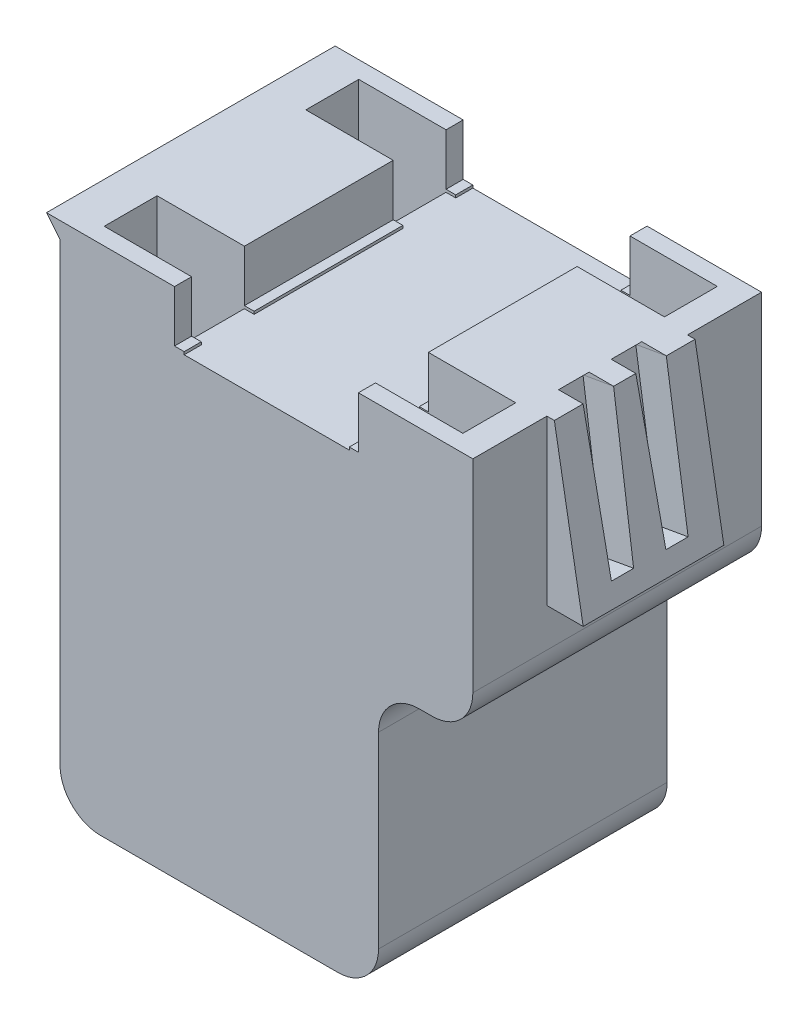
SolidWorks part; units mm, degrees
ref_plane "Alzado" through (0, 0, 0) normal (0, 0, 1) x (1, 0, 0)
ref_plane "Planta" through (0, 0, 0) normal (0, 1, 0) x (1, 0, 0)
ref_plane "Vista lateral" through (0, 0, 0) normal (1, 0, 0) x (0, 0, -1)
sketch "Croquis1" plane through (0, 0, 0) normal (0, 0, 1) x (1, 0, 0)
  line L1 (-15.23, 18.9) -> (-6.785, 18.9)
  line L2 (-15.23, 18.9) -> (-15.23, -15.9)
  line L3 (-12.23, -18.9) -> (5.27, -18.9)
  line L4 (15.23, 18.9) -> (15.23, 3.95)
  line L5 (-15.23, 18.9) -> (8.27, -10.2628) construction
  line L6 (-15.23, -18.9) -> (15.23, 18.9) construction
  line L7 (-6.785, 15.1) -> (6.785, 15.1)
  line L8 (-6.785, 15.1) -> (-6.785, 18.9)
  line L9 (6.785, 15.1) -> (6.785, 18.9)
  line L10 (6.785, 18.9) -> (15.23, 18.9)
  line L11 (8.27, -15.9) -> (8.27, -2.05)
  line L12 (11.27, 0.95) -> (12.23, 0.95)
  arc A0 (15.23, 3.95) -> (12.23, 0.95) centre (12.23, 3.95) cw
  arc A1 (11.27, 0.95) -> (8.27, -2.05) centre (11.27, -2.05) ccw
  arc A2 (5.27, -18.9) -> (8.27, -15.9) centre (5.27, -15.9) ccw
  arc A3 (-12.23, -18.9) -> (-15.23, -15.9) centre (-12.23, -15.9) cw
  point P0 (0, 0)
  point P17 (8.27, 0.95)
  point P20 (8.27, -18.9)
  dimension "D1" = 3
  dimension "D2" = 30.46
  dimension "D4" = 19.85
extrude "Saliente-Extruir1" add sketch "Croquis1" along normal blind 21.3
sketch "Croquis2" plane through (0, 0, 0) normal (0, 0, -1) x (-1, 0, 0)
  line L0 (-15.23, 18.9) -> (-15.7844, 18.9)
  line L1 (-15.7844, 18.9) -> (-17.91, 6.8)
  line L2 (-15.23, 6.8) -> (-17.91, 6.8)
  line L3 (-15.23, 3.95) -> (-15.23, 18.9) construction
  line L4 (-15.23, 18.9) -> (-15.23, 6.8)
extrude "Saliente-Extruir2" add sketch "Croquis2" against normal through all
sketch "Croquis3" plane through (0, 0, 0) normal (0, 0, -1) x (-1, 0, 0)
  line L0 (-15.23, 6.8) -> (-15.23, 18.9)
  line L1 (-15.7844, 18.9) -> (-6.785, 18.9) construction
  line L2 (-15.23, 18.9) -> (-15.7844, 18.9)
  line L3 (-15.7844, 18.9) -> (-17.91, 6.8)
  line L4 (-17.91, 6.8) -> (-15.23, 6.8)
extrude "Cortar-Extruir1" cut sketch "Croquis3" against normal blind 5.46
sketch "Croquis4" plane through (0, 0, 21.3) normal (0, 0, 1) x (1, 0, 0)
  line L0 (17.91, 6.8) -> (15.23, 6.8)
  line L1 (17.91, 6.8) -> (15.7844, 18.9)
  line L2 (15.23, 6.8) -> (15.23, 18.9)
  line L3 (15.23, 18.9) -> (15.7844, 18.9)
extrude "Cortar-Extruir3" cut sketch "Croquis4" against normal blind 5.46
sketch "Croquis5" plane through (18.5326, 3.2556, 0) normal (0.9849, 0.173, 0) x (0, 0, -1)
  line L0 (-13.72, 15.8839) -> (-13.72, 16.1973)
  line L3 (-15.84, 15.8839) -> (-5.46, 15.8839) construction
  line L4 (-13.72, 16.1973) -> (-11.47, 16.1973)
  line L6 (-11.47, 16.1973) -> (-11.47, 15.8839)
  line L7 (-9.83, 15.8839) -> (-9.83, 16.1973)
  line L8 (-13.72, 15.8839) -> (-13.48, 5.1987)
  line L9 (-13.48, 5.1987) -> (-11.84, 5.1987)
  line L10 (-7.58, 15.8839) -> (-7.82, 5.1987)
  line L11 (-7.82, 5.1987) -> (-9.46, 5.1987)
  line L12 (-9.83, 16.1973) -> (-7.58, 16.1973)
  line L13 (-11.47, 15.8839) -> (-11.84, 5.1987)
  line L14 (-9.83, 15.8839) -> (-9.46, 5.1987)
  line L15 (-7.58, 16.1973) -> (-7.58, 15.8839)
  dimension "D4" = 1.64
extrude "Cortar-Extruir4" cut sketch "Croquis5" against normal blind 2.29
sketch "Croquis6" plane through (0, 18.9, 0) normal (0, 1, 0) x (1, 0, 0)
  line L2 (13.23, -20.0378) -> (13.23, -16.1378)
  line L3 (-13.23, -1.2622) -> (-6.0702, -1.2622)
  line L4 (-13.23, -1.2622) -> (-13.23, -5.1622)
  line L5 (-13.23, -5.1622) -> (-6.0702, -5.1622)
  line L6 (13.23, -1.2622) -> (13.23, -5.1622)
  line L8 (-13.23, -16.1378) -> (-6.0702, -16.1378)
  line L9 (-13.23, -20.0378) -> (-13.23, -16.1378)
  line L10 (-13.23, -20.0378) -> (-6.0702, -20.0378)
  line L11 (6.785, 0) -> (-6.785, 0) construction
  line L12 (-6.0702, 0) -> (6.1154, 0)
  line L13 (-6.0702, 0) -> (-6.0702, -1.2622)
  line L14 (-6.0702, -21.7081) -> (6.1154, -21.7081)
  line L15 (6.1154, 0) -> (6.1154, -1.2622)
  line L16 (-6.0702, -5.1622) -> (-6.0702, -16.1378)
  line L17 (6.1154, -1.2622) -> (13.23, -1.2622)
  line L18 (6.1154, -5.1622) -> (13.23, -5.1622)
  line L19 (6.1154, -16.1378) -> (13.23, -16.1378)
  line L20 (-6.0702, -20.0378) -> (-6.0702, -21.7081)
  line L21 (6.1154, -20.0378) -> (13.23, -20.0378)
  line L22 (6.1154, -20.0378) -> (6.1154, -21.7081)
  line L23 (6.1154, -5.1622) -> (6.1154, -16.1378)
  dimension "D1" = 3.9
extrude "Cortar-Extruir5" cut sketch "Croquis6" against normal blind 4
sketch "Croquis7" plane through (0, 14.9, 0) normal (0, 1, 0) x (1, 0, 0)
  line L1 (-13.23, -5.1622) -> (-6.0702, -5.1622) construction
  line L2 (-13.23, -1.2622) -> (-6.7921, -1.2622)
  line L3 (-13.23, -1.2622) -> (-13.23, -5.1622)
  line L4 (-13.23, -5.1622) -> (-6.7921, -5.1622)
  line L5 (-6.7921, -1.2622) -> (-6.7921, -5.1622)
  line L6 (13.23, -1.2622) -> (6.1154, -1.2622) construction
  line L7 (6.785, -1.2622) -> (13.23, -1.2622)
  line L8 (6.785, -1.2622) -> (6.785, -5.1622)
  line L9 (6.785, -5.1622) -> (13.23, -5.1622)
  line L10 (13.23, -1.2622) -> (13.23, -5.1622)
  line L11 (6.1154, -1.2622) -> (6.785, -1.2622) construction
  line L13 (13.23, -20.0378) -> (13.23, -16.1378)
  line L14 (6.785, -16.1378) -> (13.23, -16.1378)
  line L15 (6.785, -20.0378) -> (6.785, -16.1378)
  line L16 (6.785, -20.0378) -> (13.23, -20.0378)
  line L17 (-6.7921, -20.0378) -> (-6.7921, -16.1378)
  line L18 (-13.23, -16.1378) -> (-6.7921, -16.1378)
  line L19 (-13.23, -20.0378) -> (-13.23, -16.1378)
  line L20 (-13.23, -20.0378) -> (-6.7921, -20.0378)
extrude "Cortar-Extruir6" cut sketch "Croquis7" against normal blind 12
sketch "Croquis10" plane through (0, 0, 21.3) normal (0, 0, 1) x (1, 0, 0)
  line L0 (-15.23, 18.9) -> (-16.23, 18.9)
  line L1 (-16.23, 18.9) -> (-15.23, 17.6719)
  line L2 (-15.23, 18.9) -> (-15.23, -15.9) construction
  line L17 (6.785, 15.1) -> (6.1154, 15.1)
  line L18 (6.1154, 15.1) -> (6.1154, 14.9)
  line L19 (6.1154, 14.9) -> (-6.0702, 14.9)
  line L20 (-6.0702, 14.9) -> (-6.0702, 15.1)
  line L21 (-6.0702, 15.1) -> (-6.785, 15.1)
  line L22 (-6.785, 15.1) -> (-6.785, 18.9)
  line L23 (-6.785, 18.9) -> (-15.23, 18.9)
  line L24 (-15.23, 18.9) -> (-15.23, -15.9)
  line L25 (-12.23, -18.9) -> (5.27, -18.9)
  line L26 (8.27, -15.9) -> (8.27, -2.05)
  line L27 (11.27, 0.95) -> (12.23, 0.95)
  line L28 (15.23, 3.95) -> (15.23, 18.9)
  line L29 (15.23, 18.9) -> (6.785, 18.9)
  line L30 (6.785, 18.9) -> (6.785, 15.1)
  line L38 (-15.23, 18.9) -> (-15.23, 17.6719)
  arc A4 (-15.23, -15.9) -> (-12.23, -18.9) centre (-12.23, -15.9) ccw
  arc A5 (5.27, -18.9) -> (8.27, -15.9) centre (5.27, -15.9) ccw
  arc A6 (11.27, 0.95) -> (8.27, -2.05) centre (11.27, -2.05) ccw
  arc A7 (12.23, 0.95) -> (15.23, 3.95) centre (12.23, 3.95) ccw
  dimension "D1" = 1
  dimension "D2" = 0
extrude "Saliente-Extruir3" add sketch "Croquis10" against normal through all
sketch "Croquis11" plane through (0, 0, 0) normal (0, 0, -1) x (-1, 0, 0)
  line L0 (0, -3.8906) -> (10.1881, -3.8906) construction
  text T0 "SCT013" font "Century Gothic" height in points 7
extrude "Cortar-Extruir8" cut sketch "Croquis11" against normal blind 0.01
sketch "Croquis13" plane through (0, 0, 0) normal (0, 0, -1) x (-1, 0, 0)
  line L0 (-5.0354, -7.5851) -> (11.1754, -7.5851) construction
  text T0 "   100A : 50 mA" font "Century Gothic" height in points 6
extrude "Cortar-Extruir10" cut sketch "Croquis13" against normal blind 0.01
ref_point "Punto1"
ref_plane "Plano6" through (0, 0, 10.65) normal (0, 0, -1) x (-1, 0, 0)
sketch "Croquis24" [suppressed] plane through (0, 0, 10.65) normal (0, 0, -1) x (-1, 0, 0)
  spline S0 degree 3 poles (9.6199, -18.9) (6.344, -37.1232) (25.9288, -34.7825) (74.1833, -24.0324) (77.5295, -44.1652) knots 0 0 0 0 0.529362 1 1 1 1
sketch "Croquis25" [suppressed] plane through (0, -18.9, 0) normal (0, -1, 0) x (1, 0, 0)
  circle A0 centre (-9.6199, 10.65) radius 1
  dimension "D1" = 2
